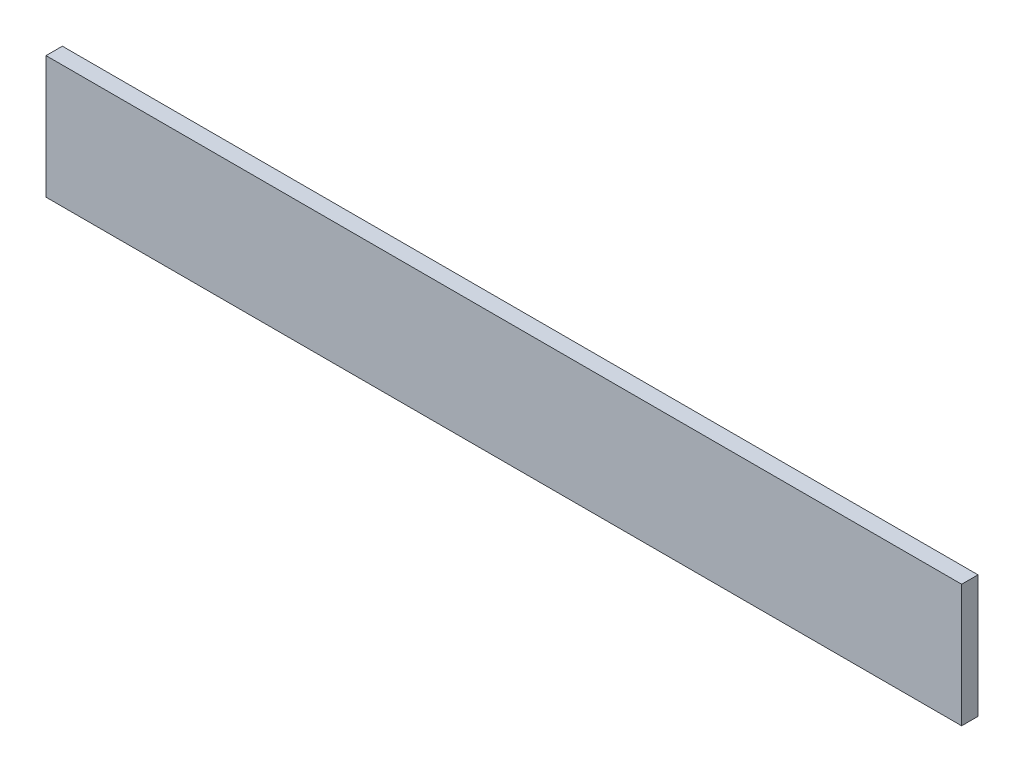
SolidWorks part; units mm, degrees
ref_plane "Ebene vorne" through (0, 0, 0) normal (0, 0, 1) x (1, 0, 0)
ref_plane "Ebene oben" through (0, 0, 0) normal (0, 1, 0) x (1, 0, 0)
ref_plane "Ebene rechts" through (0, 0, 0) normal (1, 0, 0) x (0, 0, -1)
sketch "Skizze1" plane through (0, 0, 0) normal (0, 0, 1) x (-1, 0, 0)
  line L8 (0, 0) -> (112, 0)
  line L9 (112, 0) -> (112, 15)
  line L10 (112, 15) -> (0, 15)
  line L11 (0, 15) -> (0, 0)
  dimension "D1" = 112
  dimension "D2" = 15
extrude "Aufsatz-Linear austragen1" add sketch "Skizze1" along normal blind 2
